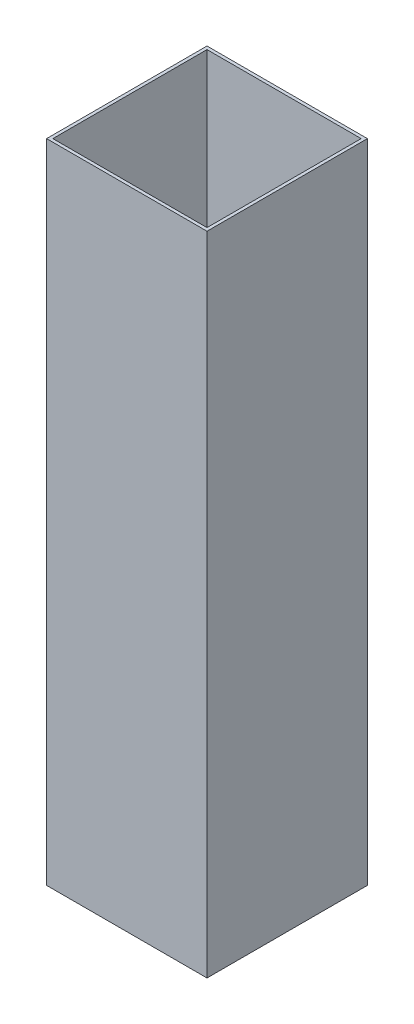
SolidWorks part; units mm, degrees
ref_plane "Front Plane" through (0, 0, 0) normal (0, 0, 1) x (1, 0, 0)
ref_plane "Top Plane" through (0, 0, 0) normal (0, 1, 0) x (1, 0, 0)
ref_plane "Right Plane" through (0, 0, 0) normal (1, 0, 0) x (0, 0, -1)
sketch "Sketch2" plane through (0, 0, 0) normal (0, 1, 0) x (1, 0, 0)
  line L1 (-38.0355, 20.9965) -> (23.9645, 20.9965)
  line L2 (-38.0355, 20.9965) -> (-38.0355, -41.0035)
  line L3 (-38.0355, -41.0035) -> (23.9645, -41.0035)
  line L4 (23.9645, 20.9965) -> (23.9645, -41.0035)
  dimension "D1" = 62
  dimension "D2" = 62
extrude "Boss-Extrude1" add sketch "Sketch2" along normal blind 250
shell "Shell1" thickness 1.2
